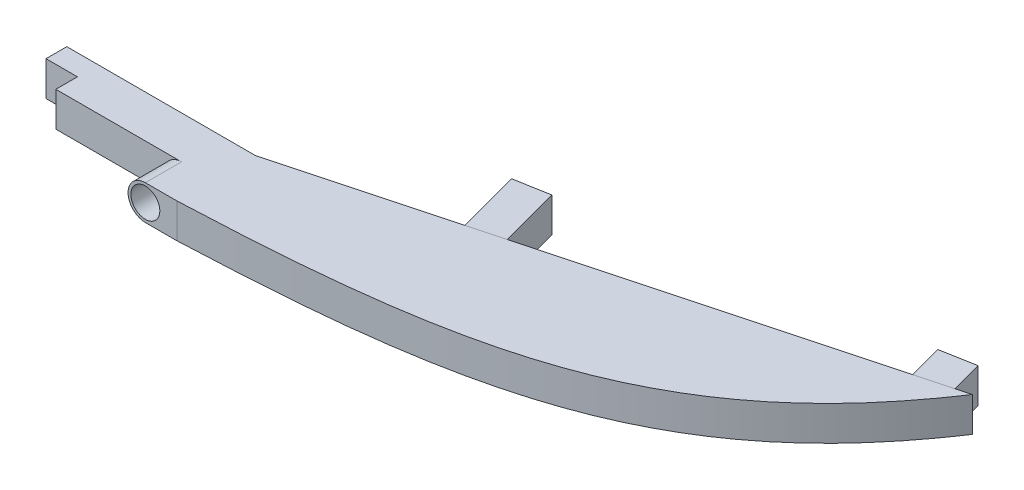
SolidWorks part; units mm, degrees
ref_plane "Alzado" through (0, 0, 0) normal (0, 0, 1) x (1, 0, 0)
ref_plane "Planta" through (0, 0, 0) normal (0, 1, 0) x (1, 0, 0)
ref_plane "Vista lateral" through (0, 0, 0) normal (1, 0, 0) x (0, 0, -1)
sketch "Croquis2" plane through (0, 0, 0) normal (0, 1, 0) x (1, 0, 0)
  line L0 (0, 0) -> (90, 0) construction
  line L1 (0, 0) -> (0, 12.5)
  line L2 (90, 0) -> (90, 39) construction
  line L3 (0, 12.5) -> (90, 36.6154)
  spline S0 degree 4 poles (-9.0154, -0.3049) (-8.717, -0.2963) (-8.098, -0.278) (-7.171, -0.253) (-5.1209, -0.1858) (-3.7226, -0.1427) (-0.7631, -0.031) (0.4662, 0.018) (2.9737, 0.1251) (4.5401, 0.2003) (6.5666, 0.3007) (8.3253, 0.3977) (10.2393, 0.5087) (12.0657, 0.6246) (14.4015, 0.7831) (17.1746, 0.9915) (20.4243, 1.2671) (24.124, 1.6319) (28.7465, 2.1606) (34.1867, 2.9164) (39.5992, 3.8695) (44.9594, 5.0771) (49.3618, 6.2804) (52.9107, 7.4009) (56.4082, 8.6739) (59.8414, 10.1115) (63.1969, 11.723) (66.46, 13.5145) (69.6167, 15.4877) (72.6542, 17.6398) (75.5626, 19.9636) (78.4114, 22.5164) (80.6372, 24.7501) (82.3142, 26.5769) (83.5002, 27.9419) (84.1665, 28.7295) (84.8247, 29.5295) (85.4679, 30.3306) (86.1096, 31.1529) (86.7258, 31.9596) (87.3592, 32.8149) (87.9353, 33.6053) (88.5854, 34.5294) (89.0773, 35.2347) (89.8261, 36.3501) (90.1738, 36.8773) (90.9035, 38.0031) (91.3552, 38.7262) (91.9126, 39.6241) (92.3432, 40.3399) (92.8683, 41.2207) (93.3254, 42.0073) (93.791, 42.8213) (94.2413, 43.6262) (94.6008, 44.2772) (94.8664, 44.7654) (95.0423, 45.0919) (95.13, 45.2553) knots 0 0 0 0 0 0.009318 0.018636 0.037271 0.055907 0.074543 0.089942 0.105341 0.12074 0.13614 0.151539 0.166938 0.182337 0.197736 0.228535 0.259333 0.290131 0.32093 0.382526 0.441205 0.472004 0.502802 0.5336 0.564399 0.595197 0.625995 0.656794 0.687592 0.71839 0.749189 0.779987 0.814189 0.82274 0.83129 0.839841 0.848391 0.856942 0.865492 0.874043 0.882593 0.891144 0.899694 0.908245 0.916795 0.925316 0.933837 0.942358 0.950879 0.957019 0.963159 0.975439 0.98158 0.98772 0.99386 1 1 1 1 1 construction
  spline S1 degree 4 poles (0, 0) (0.3914, 0.0158) (1.187, 0.0488) (2.9737, 0.1251) (4.5401, 0.2003) (6.5666, 0.3007) (8.3253, 0.3977) (10.2393, 0.5087) (12.0657, 0.6246) (14.4015, 0.7831) (17.1746, 0.9915) (20.4243, 1.2671) (24.124, 1.6319) (28.7465, 2.1606) (34.1867, 2.9164) (39.5992, 3.8695) (44.9594, 5.0771) (49.3618, 6.2804) (52.9107, 7.4009) (56.4082, 8.6739) (59.8414, 10.1115) (63.1969, 11.723) (66.46, 13.5145) (69.6167, 15.4877) (72.6542, 17.6398) (75.5626, 19.9636) (78.4114, 22.5164) (80.6372, 24.7501) (82.3142, 26.5769) (83.5002, 27.9419) (84.1665, 28.7295) (84.8247, 29.5295) (85.4679, 30.3306) (86.1096, 31.1529) (86.7258, 31.9596) (87.3592, 32.8149) (87.9353, 33.6053) (88.5854, 34.5294) (89.0773, 35.2347) (89.6394, 36.072) (89.8802, 36.4339) (90, 36.6154) knots 0.074543 0.074543 0.074543 0.074543 0.074543 0.089942 0.105341 0.12074 0.13614 0.151539 0.166938 0.182337 0.197736 0.228535 0.259333 0.290131 0.32093 0.382526 0.441205 0.472004 0.502802 0.5336 0.564399 0.595197 0.625995 0.656794 0.687592 0.71839 0.749189 0.779987 0.814189 0.82274 0.83129 0.839841 0.848391 0.856942 0.865492 0.874043 0.882593 0.891144 0.899694 0.908245 0.916795 0.916795 0.916795 0.916795 0.916795
  dimension "D4" = 36.6154
  dimension "D2" = 12.5
  dimension "D3" = 90
extrude "Saliente-Extruir1" add sketch "Croquis2" along normal blind 5.5
sketch "Croquis3" plane through (0, 0, 0) normal (-1, 0, 0) x (0, 0, 1)
  line L0 (0, 5.5) -> (0, 0) construction
  line L1 (-12.5, 0) -> (0, 0)
  line L2 (-12.5, 0) -> (-12.5, 5.5)
  line L3 (-12.5, 5.5) -> (0, 5.5)
  line L4 (0, 0) -> (0, 5.5)
  line L5 (-12.5, 0) -> (0, 5.5) construction
  line L6 (-12.5, 5.5) -> (0, 0) construction
  line L7 (-12.5, 2.75) -> (0, 2.75) construction
  line L8 (-12.5, 5.5) -> (-12.5, 0) construction
  point P0 (-6.25, 2.75)
  dimension "D1" = 12.5
  dimension "D2" = 5.5
extrude "Saliente-Extruir2" add sketch "Croquis3" along normal blind 25
sketch "Croquis4" plane through (0, 0, -12.5) normal (0, 0, -1) x (-1, 0, 0)
  line L0 (0, 2.75) -> (25, 2.75) construction
  line L1 (0, 5.5) -> (0, 0) construction
  line L2 (25, 5.5) -> (25, 0) construction
  line L14 (25, 5.5) -> (25, 0) construction
  circle A0 centre (5, 2.75) radius 2.3
  point P28 (25, 2.75)
  dimension "D1" = 4.6
  dimension "D2" = 20
extrude "Cortar-Extruir3" cut sketch "Croquis4" against normal blind 12.5 contours A0
sketch "Croquis5" plane through (0, 0, 0) normal (0, 0, 1) x (1, 0, 0)
  line L0 (-25, 5.5) -> (-16, 5.5)
  line L4 (-5, 0) -> (-25, 0)
  line L5 (-25, 0) -> (-25, 5.5)
  circle A0 centre (-5, 2.75) radius 2.75
  line M8 (0, 5.5) -> (-25, 5.5)
  line M9 (-25, 5.5) -> (-25, 0)
  line M10 (-25, 0) -> (0, 0)
  dimension "D2" = 5.5
extrude "Cortar-Extruir2" cut sketch "Croquis5" against normal blind 5.75 contours A0 M8 M9 M10
sketch "Croquis6" plane through (-25, 0, 0) normal (-1, 0, 0) x (0, 0, 1)
  line L0 (-9.1875, 5.5) -> (-9.1875, -0.5)
  line L1 (-12.625, -0.5) -> (-5.75, -0.5)
  line L2 (-12.625, -0.5) -> (-12.625, 5.5)
  line L3 (-12.625, 5.5) -> (-5.75, 5.5)
  line L4 (-5.75, -0.5) -> (-5.75, 5.5)
  line L5 (-12.625, -0.5) -> (-5.75, 5.5) construction
  line L6 (-12.625, 5.5) -> (-5.75, -0.5) construction
  point P0 (-9.1875, 2.5)
  point P4 (-9.1875, 2.5)
extrude "Saliente-Extruir3" add sketch "Croquis6" along normal blind 5
sketch "Croquis9" plane through (0, 5.5, 0) normal (0, 1, 0) x (1, 0, 0)
  line L0 (0, 12.5) -> (0, 15)
  line L1 (0, 15) -> (-30, 15)
  line L2 (-30, 15) -> (-30, 20)
  line L3 (0, 12.5) -> (90, 36.6154)
  line L4 (0, 12.5) -> (90, 36.6154)
  line L5 (90, 36.6154) -> (88.7059, 41.4451)
  line L6 (88.7059, 41.4451) -> (-30, 20)
  line L7 (28.9778, 20.2646) -> (26.3223, 30.175) construction
  line L8 (26.3215, 19.5528) -> (23.6067, 29.6844)
  line L9 (31.6341, 20.9763) -> (29.0378, 30.6656)
  line L10 (85.1704, 35.3213) -> (83.7685, 40.5531) construction
  line L11 (87.8267, 36.0331) -> (86.4841, 41.0437)
  line L12 (82.5141, 34.6096) -> (81.053, 40.0625)
  dimension "D1" = 2.5
  dimension "D2" = 30
  dimension "D3" = 5
  dimension "D4" = 5
  dimension "D5" = 30
  dimension "D6" = 2.75
  dimension "D7" = 2.75
  dimension "D8" = 5
  dimension "D9" = 2.75
  dimension "D10" = 2.75
extrude "Saliente-Extruir6" add sketch "Croquis9" against normal blind 5.5 separate body contours L12 L4 L11 L6 | L4 L9 L6 L8
equation "\"D1@Croquis2\" = \"A_BASE\""
equation "\"D3@Croquis2\" = \"L_ALETA\""
equation "\"D2@Croquis2\" = \"A_BASE\""
equation "\"D1@Saliente-Extruir1\"=\"E_ALETA\""
equation "\"D1@Croquis3\"=\"A_BASE\""
equation "\"D2@Croquis3\"  = \"E_ALETA\""
equation "\"D1@Saliente-Extruir2\"=\"L_CAJA\""
equation "\"D1@Croquis4\"=\"R_SONDA\" * 2 +\"TOLERANCIA\""
equation "\"D2@Croquis4\"=\"D_SONDA\""
equation "\"A_BASE\"= \"L_DIE\" -  \"E_CAJA\""
equation "\"E_CE_SONDA\"= 0.1"
equation "\"L_DIE_SONDA\"= ( \"GAP_ALETAS\" / 4 )"
equation "\"D1@Croquis5\" = \"L_CONC\""
equation "\"D1@Cortar-Extruir2\" = \"A_BASE\" - ( ( \"A_CAJA\" - \"A_CONC\" ) / 2 )"
equation "\"OFFSET_SONDA_2\"= 1.000000"
equation "\"K\"= 1.5"
equation "\"L_CE\"= \"L_DIE\""
equation "\"D1@Croquis8\" = \"OFFSET_SONDA\""
equation "\"D1@Cortar-Extruir4\" = \"E_BASE\""
equation "\"D4@Croquis2\" = ( ( sqr ( 13 ) - 3 ) * \"W_ALETA\" ) / 8"
equation "\"A_ALETA\"= ( ( ( tan ( \"ANG_ALETA\" ) ) * \"L_ALETA\" ) + \"A_BASE\" )"
equation "\"A_CAJA\"= ( 2 * \"A_BASE\" ) + \"GAP_ALETAS\""
equation "\"L_ALETA\"=90.000000"
equation "\"TAU_ALETA\"= ( \"L_ALETA\" / ( log ( ( \"A_ALETA\" ) + 1 ) ) )"
equation "\"E_ALETA\"=5.5"
equation "\"R_SONDA\"= 2.05"
equation "\"D_SONDA\"=20.000000"
equation "\"L_CAJA\"=25.000000"
equation "\"E_CAJA\"= 2.5"
equation "\"W_CAJA\"= \"A_CAJA\" * \"CONST_CAJA\""
equation "\"W_CONC\"= ( \"W_CAJA\" / \"CONST_CONC\" ) "
equation "\"A_CONC\"= ( \"A_CAJA\" / \"CONST_CONC\" )"
equation "\"L_CONC\"= \"D_SONDA\" - \"OFFSET_CONC\""
equation "\"W_ALETA\"=70.000000"
equation "\"GAP_ALETAS\"=2"
equation "\"R_C_SONDA\"= 0.63"
equation "\"CONST_CONC\"=2.000000"
equation "\"L_DIE\"= 15"
equation "\"L_CI\"= 18"
equation "\"CONST_CAJA\"=2.000000"
equation "\"ANG_ALETA\"=15.000000"
equation "\"TOLERANCIA\"= 0.5"
equation "\"A_BASE\"= ( \"L_DIE\" - \"E_CAJA\" )"
equation "\"D1@Cortar-Extruir3\" = \"A_BASE\""
equation "\"OFFSET_CONC\"= ( 2 * \"R_TORNILLO\" )"
equation "\"R_TORNILLO\"=2.600000"
equation "\"D1@Saliente-Extruir3\"=\"E_CAJA\"*2"
equation "\"D1@Croquis9\"=\"E_CAJA\""
equation "\"D2@Croquis9\"=\"L_CAJA\"+\"E_CAJA\"*2"
equation "\"D3@Croquis9\"=\"E_CAJA\"*2"
equation "\"D4@Croquis9\"=\"E_CAJA\"*2"
equation "\"D6@Croquis9\" = \"E_ALETA\" / 2"
equation "\"D7@Croquis9\"=\"E_ALETA\"/2"
equation "\"D9@Croquis9\"=\"E_ALETA\"/2"
equation "\"D10@Croquis9\"=\"E_ALETA\"/2"
equation "\"D1@Saliente-Extruir6\"=\"E_ALETA\""
equation "\"ALARGUE\"=15"
